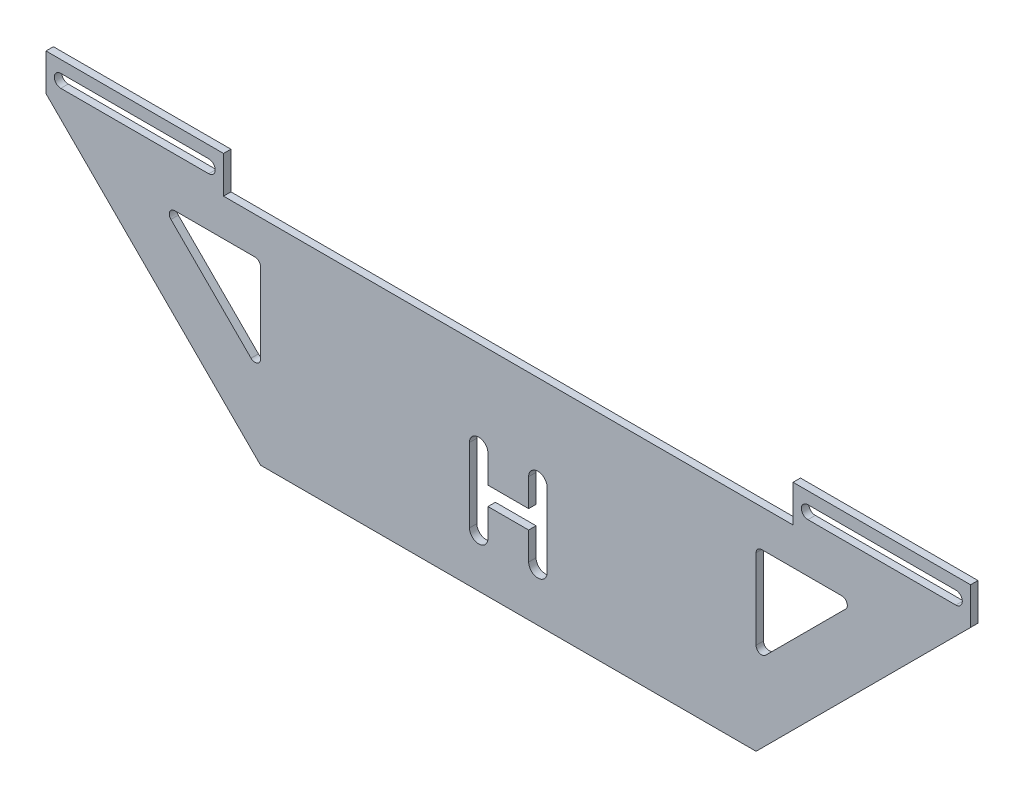
SolidWorks part; units mm, degrees
material "6061 合金"
ref_plane "前视基准面" through (0, 0, 0) normal (0, 0, 1) x (1, 0, 0)
ref_plane "上视基准面" through (0, 0, 0) normal (0, 1, 0) x (1, 0, 0)
ref_plane "右视基准面" through (0, 0, 0) normal (1, 0, 0) x (0, 0, -1)
sketch "草图1" plane through (0, 0, 0) normal (0, 0, 1) x (1, 0, 0)
  line L0 (-77, 30) -> (-77, 0)
  line L1 (-77, 0) -> (77, 0)
  line L2 (77, 0) -> (77, 30)
  line L3 (-77, 30) -> (-125, 30)
  line L5 (-67, -58) -> (67, -58)
  line L7 (125, 30) -> (77, 30)
  line L8 (0, 0) -> (0, -58) construction
  line L9 (-121, 25) -> (-81, 25) construction
  line L10 (-121, 25) -> (-121, 5) construction
  line L11 (-121, 5) -> (-81, 5) construction
  line L12 (-81, 25) -> (-81, 5) construction
  line L13 (81, 25) -> (81, 5) construction
  line L14 (121, 5) -> (81, 5) construction
  line L15 (121, 25) -> (121, 5) construction
  line L16 (121, 25) -> (81, 25) construction
  line L19 (-125, 30) -> (-125, 0)
  line L20 (-125, 0) -> (-67, -58)
  line L21 (67, -58) -> (125, 0)
  line L22 (125, 0) -> (125, 30)
  circle A0 centre (-121, 25) radius 1.5
  circle A1 centre (-81, 25) radius 1.5
  circle A2 centre (-81, 5) radius 1.5
  circle A3 centre (-121, 5) radius 1.5
  circle A4 centre (121, 5) radius 1.5
  circle A5 centre (81, 5) radius 1.5
  circle A6 centre (81, 25) radius 1.5
  circle A7 centre (121, 25) radius 1.5
  point P4 (0, 0)
  dimension "D5" = 3
  dimension "D1" = 30
  dimension "D2" = 154
  dimension "D3" = 58
  dimension "D4" = 48
  dimension "D6" = 5
  dimension "D7" = 5
  dimension "D8" = 4
  dimension "D9" = 4
  dimension "D14" = 45
extrude "凸台-拉伸1" add sketch "草图1" along normal blind 2
sketch "草图3" plane through (0, 0, 2) normal (0, 0, 1) x (1, 0, 0)
  line L0 (125, 0) -> (125, 30) construction
  line L1 (-125, 30) -> (125, 30)
  line L2 (-125, 30) -> (-125, 10)
  line L3 (-125, 10) -> (125, 10)
  line L4 (125, 30) -> (125, 10)
  circle A0 centre (121, 5) radius 1.5 construction
  dimension "D1" = 5
extrude "切除-拉伸2" cut sketch "草图3" against normal through all
sketch "草图4" plane through (0, 0, 2) normal (0, 0, 1) x (1, 0, 0)
  line L0 (-91.2261, -12.5607) -> (-69.5607, -34.2261)
  line L1 (-67, -33.1655) -> (-67, -11.5)
  line L2 (-68.5, -10) -> (-90.1655, -10)
  line L3 (77, 0) -> (-77, 0) construction
  line L4 (-125, 0) -> (-67, -58) construction
  line L5 (0, 0) -> (0, -58) construction
  line L6 (-67, -58) -> (67, -58) construction
  line L26 (68.5, -10) -> (90.1655, -10)
  line L27 (67, -33.1655) -> (67, -11.5)
  line L28 (91.2261, -12.5607) -> (69.5607, -34.2261)
  line L32 (0, 0) -> (0, -58)
  line L33 (0, -10.8561) -> (0, -58)
  line L37 (-5.5, -36.928) -> (-5.5, -44.428)
  line L41 (-5.5, -31.928) -> (5.5, -31.928)
  line L42 (-5.5, -36.928) -> (5.5, -36.928)
  line L44 (-5.5, -24.428) -> (-5.5, -31.928)
  line L45 (-10.5, -24.428) -> (-10.5, -44.428)
  line L47 (10.5, -24.428) -> (10.5, -44.428)
  line L48 (5.5, -24.428) -> (5.5, -31.928)
  line L49 (5.5, -36.928) -> (5.5, -44.428)
  arc A5 (-29.7022, -1.7005) -> (-29.9, -1.575) centre (-29, -0.375) cw
  arc A10 (-69.5607, -34.2261) -> (-67, -33.1655) centre (-68.5, -33.1655) ccw
  arc A11 (-67, -11.5) -> (-68.5, -10) centre (-68.5, -11.5) ccw
  arc A12 (-91.2261, -12.5607) -> (-90.1655, -10) centre (-90.1655, -11.5) cw
  arc A13 (91.2261, -12.5607) -> (90.1655, -10) centre (90.1655, -11.5) ccw
  arc A14 (67, -11.5) -> (68.5, -10) centre (68.5, -11.5) cw
  arc A15 (69.5607, -34.2261) -> (67, -33.1655) centre (68.5, -33.1655) cw
  arc A27 (-5.5, -24.428) -> (-10.5, -24.428) centre (-8, -24.428) ccw
  arc A28 (-10.5, -44.428) -> (-5.5, -44.428) centre (-8, -44.428) ccw
  arc A29 (10.5, -24.428) -> (5.5, -24.428) centre (8, -24.428) ccw
  arc A30 (5.5, -44.428) -> (10.5, -44.428) centre (8, -44.428) ccw
  point P26 (0, -34.428)
  point P32 (-8, -34.428)
  point P37 (8, -34.428)
  point P51 (-41.5, -62.2868)
  point P54 (-24, -16)
  point P59 (-67, -10)
  point P89 (67, -10)
  point P91 (41.5, -62.2868)
  dimension "D7" = 1.5
  dimension "D1" = 10
  dimension "D2" = 15
  dimension "D5" = 6
  dimension "D8" = 29
extrude "切除-拉伸3" cut sketch "草图4" against normal through all and the other way through all
sketch "草图5" plane through (0, 0, 2) normal (0, 0, 1) x (1, 0, 0)
  line L0 (-121, 5) -> (-81, 5) construction
  line L1 (-121, 6.75) -> (-81, 6.75)
  line L2 (-121, 3.25) -> (-81, 3.25)
  line L3 (81, 5) -> (121, 5) construction
  line L4 (81, 6.75) -> (121, 6.75)
  line L5 (81, 3.25) -> (121, 3.25)
  arc A0 (-121, 6.75) -> (-121, 3.25) centre (-121, 5) ccw
  arc A1 (-81, 3.25) -> (-81, 6.75) centre (-81, 5) ccw
  arc A2 (81, 6.75) -> (81, 3.25) centre (81, 5) ccw
  arc A3 (121, 3.25) -> (121, 6.75) centre (121, 5) ccw
  point P4 (-101, 5)
  point P13 (101, 5)
extrude "切除-拉伸4" cut sketch "草图5" against normal through all
